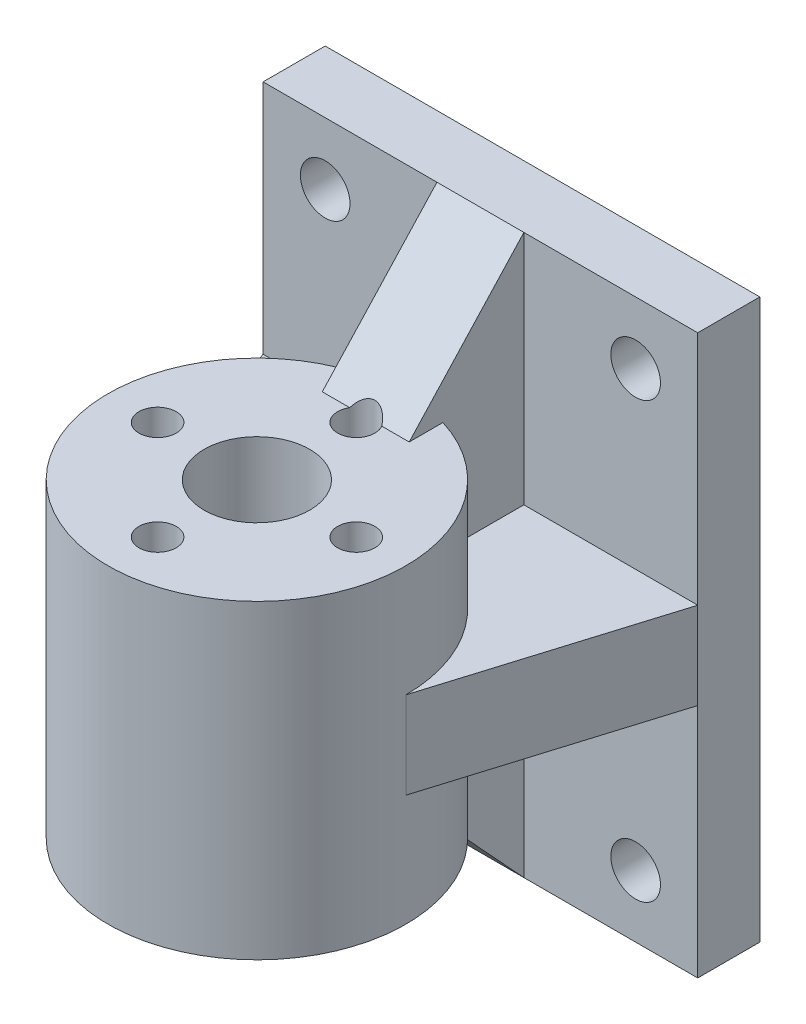
SolidWorks part; units mm, degrees
ref_plane "Płaszczyzna przednia" through (0, 0, 0) normal (0, 0, 1) x (1, 0, 0)
ref_plane "Płaszczyzna górna" through (0, 0, 0) normal (0, 1, 0) x (1, 0, 0)
ref_plane "Płaszczyzna prawa" through (0, 0, 0) normal (1, 0, 0) x (0, 0, -1)
sketch "Szkic1" plane through (0, 0, 0) normal (0, 1, 0) x (1, 0, 0)
  line L1 (17.5, 0) -> (-17.5, 0)
  line L2 (17.5, 0) -> (17.5, 5)
  line L3 (17.5, 5) -> (-17.5, 5)
  line L4 (-17.5, 0) -> (-17.5, 5)
  point P4 (0, 0)
  point P5 (0, 0)
extrude "Dodanie-wyciągnięcie1" add sketch "Szkic1" along normal blind 45
sketch "Szkic2" plane through (0, 0, 0) normal (0, 1, 0) x (1, 0, 0)
  circle A0 centre (0, -18) radius 4.25
  circle A1 centre (0, -18) radius 12
  point P3 (0, 0)
extrude "Dodanie-wyciągnięcie2" add sketch "Szkic2" along normal blind 25 from offset 10 separate body
sketch "Szkic3" plane through (-17.5, 0, 0) normal (-1, 0, 0) x (0, 0, 1)
  line L0 (0, 0) -> (0, 45)
  line L1 (0, 45) -> (9.235, 35)
  line L2 (30, 35) -> (6, 35) construction
  line L3 (9.235, 35) -> (9.235, 10)
  line L4 (6, 10) -> (30, 10) construction
  line L5 (9.235, 10) -> (0, 0)
extrude "Dodanie-wyciągnięcie3" add sketch "Szkic3" against normal blind 7 from offset 14 offset against normal yes
sketch "Szkic4" plane through (0, 0, 0) normal (0, -1, 0) x (1, 0, 0)
  line L0 (-17.5, 0) -> (-12, 18)
  line L1 (-12, 18) -> (0, 9.235)
  line L2 (3.5, 9.235) -> (-3.5, 9.235) construction
  line L3 (0, 9.235) -> (12, 18)
  line L4 (12, 18) -> (17.5, 0)
  line L5 (17.5, 0) -> (-17.5, 0)
  arc A0 (3.5, 6.5218) -> (-3.5, 6.5218) centre (0, 18) ccw construction
extrude "Dodanie-wyciągnięcie4" add sketch "Szkic4" against normal blind 7 from offset 19 offset against normal yes
sketch "Szkic5" plane through (0, 0, -5) normal (0, 0, -1) x (-1, 0, 0)
  circle A0 centre (-12.5, 40) radius 2
  circle A1 centre (12.5, 40) radius 2
  circle A2 centre (12.5, 5) radius 2
  circle A3 centre (-12.5, 5) radius 2
extrude "Wytnij-wyciągnięcie1" cut sketch "Szkic5" against normal up to next
sketch "Szkic10" plane through (0, 10, 0) normal (0, -1, 0) x (-1, 0, 0)
  circle A0 centre (-8, -18) radius 1.5
  point P2 (0, 0)
extrude "Wytnij-wyciągnięcie2" cut sketch "Szkic10" against normal up to next and the other way blind 3
pattern_circular "Szyk kołowy1" count 4 every 90 about axis through (0, 0, 18) along (0, 1, 0) of "Wytnij-wyciągnięcie2"
chamfer "Sfazowanie1" distance 1 angle 32 1 edges at (0, 10, 22.25)
